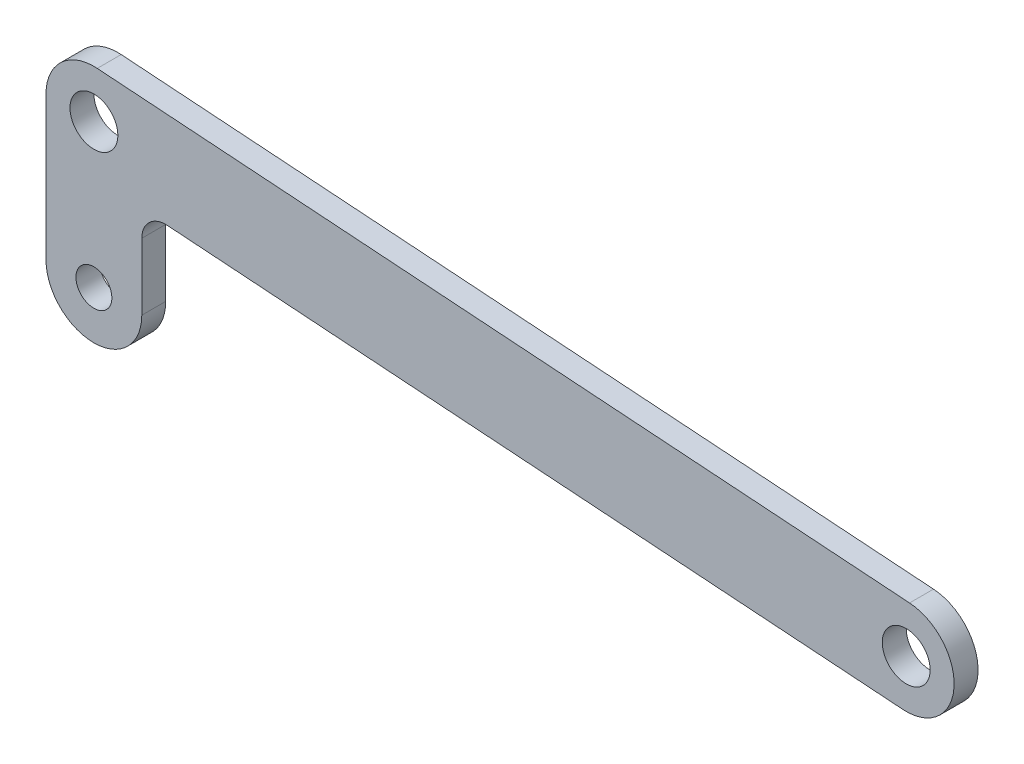
SolidWorks part; units mm, degrees
other "Marca1"
sketch "Croquis3"
ref_plane "Alzado" through (0, 0, 0) normal (0, 0, 1) x (1, 0, 0)
ref_plane "Planta" through (0, 0, 0) normal (0, 1, 0) x (1, 0, 0)
ref_plane "Vista lateral" through (0, 0, 0) normal (1, 0, 0) x (0, 0, -1)
sketch "Croquis1" plane through (0, 0, 0) normal (0, 0, 1) x (1, 0, 0)
  line L0 (0, 0) -> (0, 60) construction
  line L1 (0, 60) -> (339.1718, 36.2828) construction
  line L2 (-20, 0) -> (-20, 60)
  line L3 (20, 0) -> (20, 27.8289)
  line L4 (-1.3951, 40.0487) -> (0, 39.9512)
  line L5 (1.3951, 79.9513) -> (340.5669, 56.2341)
  line L6 (30.6976, 37.8046) -> (337.7766, 16.3315)
  line L7 (20, 58.6015) -> (20, 60)
  line L8 (20, 78.6503) -> (20, 78.958)
  circle A0 centre (0, 0) radius 7.5
  circle A2 centre (339.1718, 36.2828) radius 10
  arc A3 (-20, 0) -> (20, 0) centre (0, 0) ccw
  arc A4 (1.3951, 79.9513) -> (-20, 60) centre (0, 60) ccw
  arc A5 (337.7766, 16.3315) -> (340.5669, 56.2341) centre (339.1718, 36.2828) ccw
  arc A6 (19.9513, 58.6049) -> (20, 60) centre (0, 60) ccw
  arc A7 (-1.3951, 40.0487) -> (0, 40) centre (0, 60) ccw
  arc A8 (30.6976, 37.8046) -> (20, 27.8289) centre (30, 27.8289) ccw
  circle A10 centre (0, 60) radius 10
  dimension "D4" = 15
  dimension "D5" = 20
  dimension "D6" = 20
  dimension "D7" = 40
  dimension "D8" = 40
  dimension "D9" = 40
  dimension "D12" = 10
  dimension "D1" = 86
  dimension "D2" = 60
  dimension "D3" = 340
  dimension "D10" = 40
  dimension "D11" = 40
extrude "Saliente-Extruir1" add sketch "Croquis1" along normal blind 10
sketch "Croquis2" plane through (0, 0, 0) normal (0, 0, -1) x (-1, 0, 0)
  line L0 (0, 0) -> (0, 60) construction
  circle A0 centre (0, 60) radius 10
  dimension "D2" = 20
  dimension "D1" = 60
